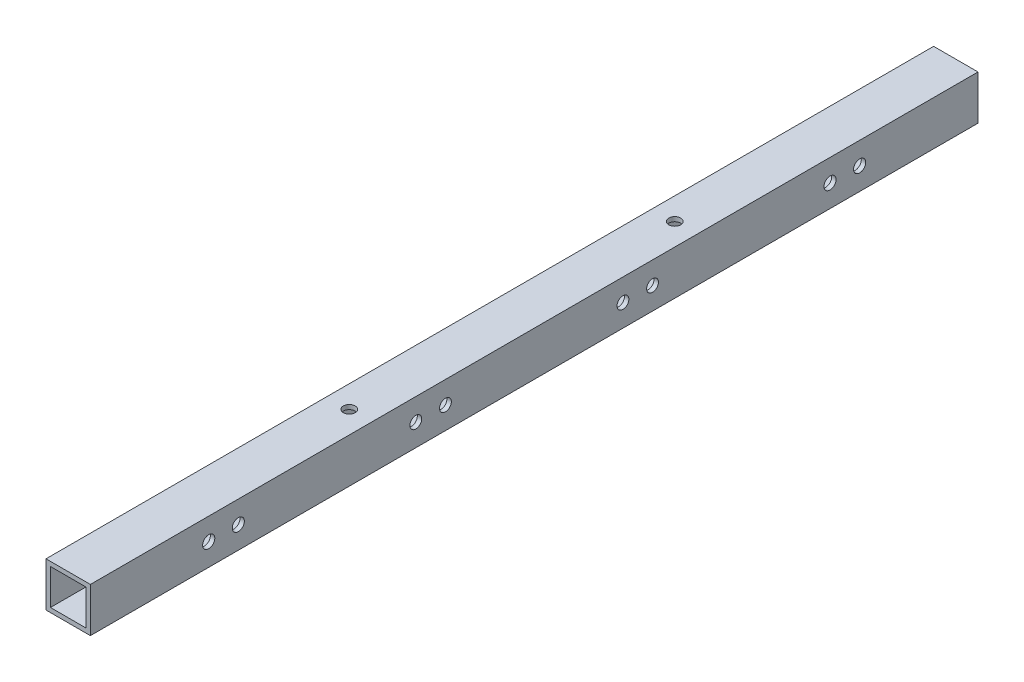
SolidWorks part; units mm, degrees
ref_plane "前视基准面" through (0, 0, 0) normal (0, 0, 1) x (1, 0, 0)
ref_plane "上视基准面" through (0, 0, 0) normal (0, 1, 0) x (1, 0, 0)
ref_plane "右视基准面" through (0, 0, 0) normal (1, 0, 0) x (0, 0, -1)
sketch "草图1" plane through (0, 0, 0) normal (0, 0, 1) x (1, 0, 0)
  line L1 (-7.5, 7.5) -> (7.5, 7.5)
  line L2 (-7.5, 7.5) -> (-7.5, -7.5)
  line L3 (-7.5, -7.5) -> (7.5, -7.5)
  line L4 (7.5, 7.5) -> (7.5, -7.5)
  line L5 (-7.5, 7.5) -> (7.5, -7.5) construction
  line L6 (-7.5, -7.5) -> (7.5, 7.5) construction
  line L7 (-6, 6) -> (6, 6)
  line L8 (-6, 6) -> (-6, -6)
  line L9 (-6, -6) -> (6, -6)
  line L10 (6, 6) -> (6, -6)
  line L11 (-6, 6) -> (6, -6) construction
  line L12 (-6, -6) -> (6, 6) construction
  point P0 (0, 0)
  point P5 (0, 0)
  dimension "D1" = 15
  dimension "D2" = 15
  dimension "D3" = 1.5
  dimension "D4" = 1.5
extrude "凸台-拉伸1" add sketch "草图1" along normal blind 300
sketch "草图2" plane through (0, 7.5, 0) normal (0, 1, 0) x (1, 0, 0)
  line L0 (-126.6708, -150) -> (152.304, -150) construction
  line L1 (0, -38.2819) -> (0, -237.3665) construction
  circle A0 centre (0, -205) radius 2
  circle A1 centre (0, -95) radius 2
  dimension "D2" = 4
  dimension "D1" = 150
  dimension "D3" = 55
extrude "切除-拉伸1" cut sketch "草图2" against normal blind 30
sketch "草图4" plane through (-7.5, 0, 0) normal (-1, 0, 0) x (0, 0, 1)
  line L0 (150, 79.3864) -> (150, -61.1557) construction
  line L1 (300, 7.5) -> (300, -7.5) construction
  line L2 (0, 7.5) -> (0, -7.5) construction
  circle A0 centre (250, 0) radius 2.05
  circle A1 centre (260, 0) radius 2.05
  circle A2 centre (40, 0) radius 2.05
  circle A3 centre (50, 0) radius 2.05
  dimension "D2" = 4.1
  dimension "D3" = 40
  dimension "D4" = 10
extrude "切除-拉伸3" cut sketch "草图4" against normal blind 120
sketch "草图5" plane through (-7.5, 0, 0) normal (-1, 0, 0) x (0, 0, 1)
  line L0 (150, 100.1406) -> (150, -106.2433) construction
  line L1 (0, 7.5) -> (0, -7.5) construction
  line L2 (300, 7.5) -> (300, -7.5) construction
  circle A0 centre (120, 0) radius 2
  circle A1 centre (110, 0) radius 2
  circle A2 centre (190, 0) radius 2
  circle A3 centre (180, 0) radius 2
  point P3 (0, 0)
  point P15 (0, 0)
  point P17 (119.9738, 0.7236)
  dimension "D4" = 4
  dimension "D1" = 80
  dimension "D3" = 10
extrude "切除-拉伸4" cut sketch "草图5" against normal blind 49
